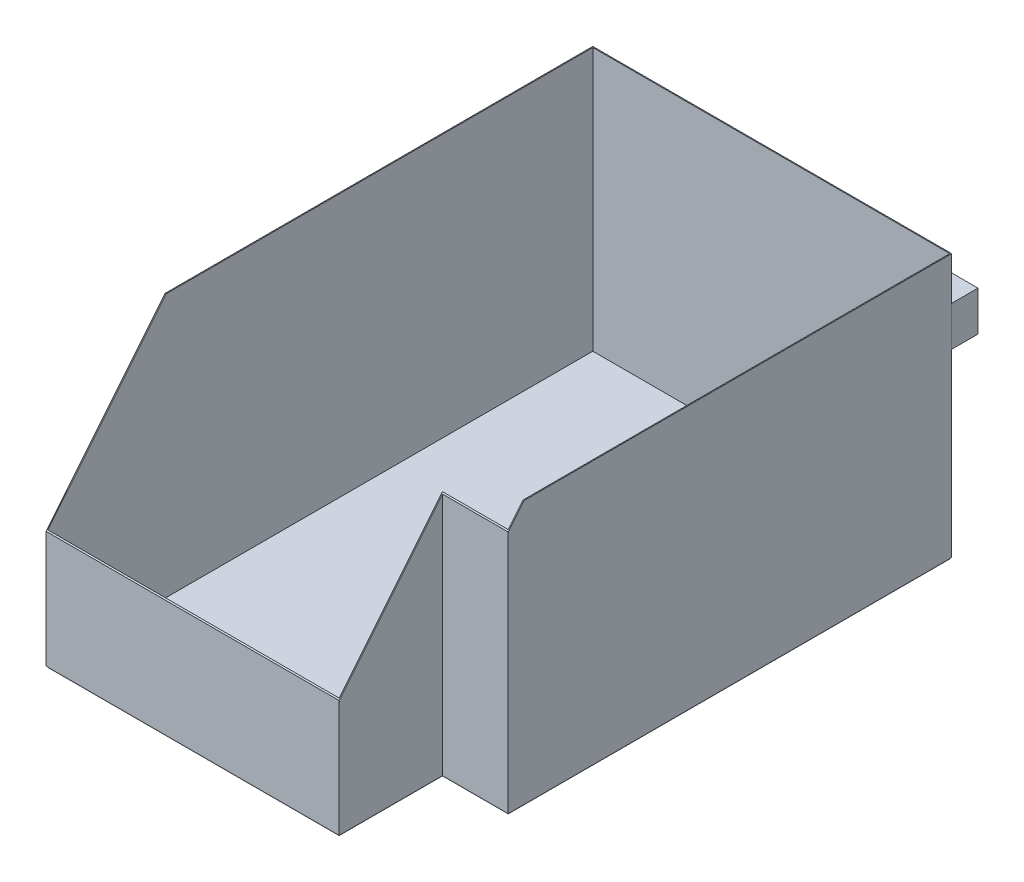
SolidWorks part; units mm, degrees
ref_plane "Front Plane" through (0, 0, 0) normal (0, 0, 1) x (1, 0, 0)
ref_plane "Top Plane" through (0, 0, 0) normal (0, 1, 0) x (1, 0, 0)
ref_plane "Right Plane" through (0, 0, 0) normal (1, 0, 0) x (0, 0, -1)
sketch "Sketch1" plane through (0, 0, 0) normal (0, 1, 0) x (1, 0, 0)
  line L1 (-147.1514, 167.8263) -> (232.8486, 167.8263)
  line L2 (-147.1514, 167.8263) -> (-147.1514, -412.1737)
  line L3 (-147.1514, -412.1737) -> (162.8486, -412.1737)
  line L4 (232.8486, 167.8263) -> (232.8486, -302.1737)
  line L6 (232.8486, -302.1737) -> (162.8486, -302.1737)
  line L7 (162.8486, -302.1737) -> (162.8486, -412.1737)
  dimension "D1" = 580
  dimension "D2" = 380
  dimension "D5" = 110
  dimension "D6" = 70
extrude "Boss-Extrude1" add sketch "Sketch1" along normal blind 1.5
sketch "Sketch2" plane through (0, 1.5, 0) normal (0, 1, 0) x (1, 0, 0)
  line L18 (-147.1514, 167.8263) -> (-147.1514, -412.1737)
  line L29 (-147.1514, -412.1737) -> (162.8486, -412.1737)
  line L30 (162.8486, -412.1737) -> (162.8486, -302.1737)
  line L31 (162.8486, -302.1737) -> (232.8486, -302.1737)
  line L32 (232.8486, -302.1737) -> (232.8486, 167.8263)
  line L33 (232.8486, 167.8263) -> (-147.1514, 167.8263)
  line L34 (-147.1514, 167.8263) -> (-147.1514, -412.1737)
  line L37 (-147.1514, -412.1737) -> (162.8486, -412.1737)
  line L38 (162.8486, -412.1737) -> (162.8486, -302.1737)
  line L39 (162.8486, -302.1737) -> (232.8486, -302.1737)
  line L40 (232.8486, -302.1737) -> (232.8486, 167.8263)
  line L41 (232.8486, 167.8263) -> (-147.1514, 167.8263)
  line L54 (-148.1514, -413.1737) -> (163.8486, -413.1737)
  line L55 (163.8486, -413.1737) -> (163.8486, -303.1737)
  line L56 (163.8486, -303.1737) -> (233.8486, -303.1737)
  line L57 (233.8486, -303.1737) -> (233.8486, 168.8263)
  line L58 (233.8486, 168.8263) -> (-148.1514, 168.8263)
  line L59 (-148.1514, 168.8263) -> (-148.1514, -413.1737)
  dimension "D1" = 0
  dimension "D2" = 1
extrude "Boss-Extrude2" add sketch "Sketch2" along normal blind 280
sketch "Sketch3" plane through (-147.1514, 0, 0) normal (-1, 0, 0) x (0, 0, 1)
  line L1 (-168.8263, 281.5) -> (413.1737, 281.5) construction
  line L4 (413.1737, 125.5281) -> (286.3951, 281.5)
  line L5 (286.3951, 281.5) -> (413.1737, 281.5)
  line L7 (413.1737, 281.5) -> (413.1737, 125.5281)
  line L8 (413.1737, 281.5) -> (413.1737, 1.5) construction
  point P1 (272.0513, 281.5)
  point P2 (413.1737, 125.5281)
  point P3 (281.4187, 281.5)
  point P10 (286.3951, 281.5)
sketch "Sketch4" plane through (0, 0, -167.8263) normal (0, 0, -1) x (-1, 0, 0)
  line L0 (-232.8486, 1.5) -> (-232.8486, 0) construction
  line L1 (-232.8486, 234.6761) -> (147.1514, 234.6761)
  line L2 (-232.8486, 234.6761) -> (-232.8486, 192.2905)
  line L3 (-232.8486, 192.2905) -> (147.1514, 192.2905)
  line L4 (147.1514, 234.6761) -> (147.1514, 192.2905)
  line L5 (147.1514, 1.5) -> (147.1514, 0) construction
extrude "Boss-Extrude3" add sketch "Sketch4" along normal blind 30
extrude "Cut-Extrude1" cut sketch "Sketch3" against normal through all both and the other way through all
